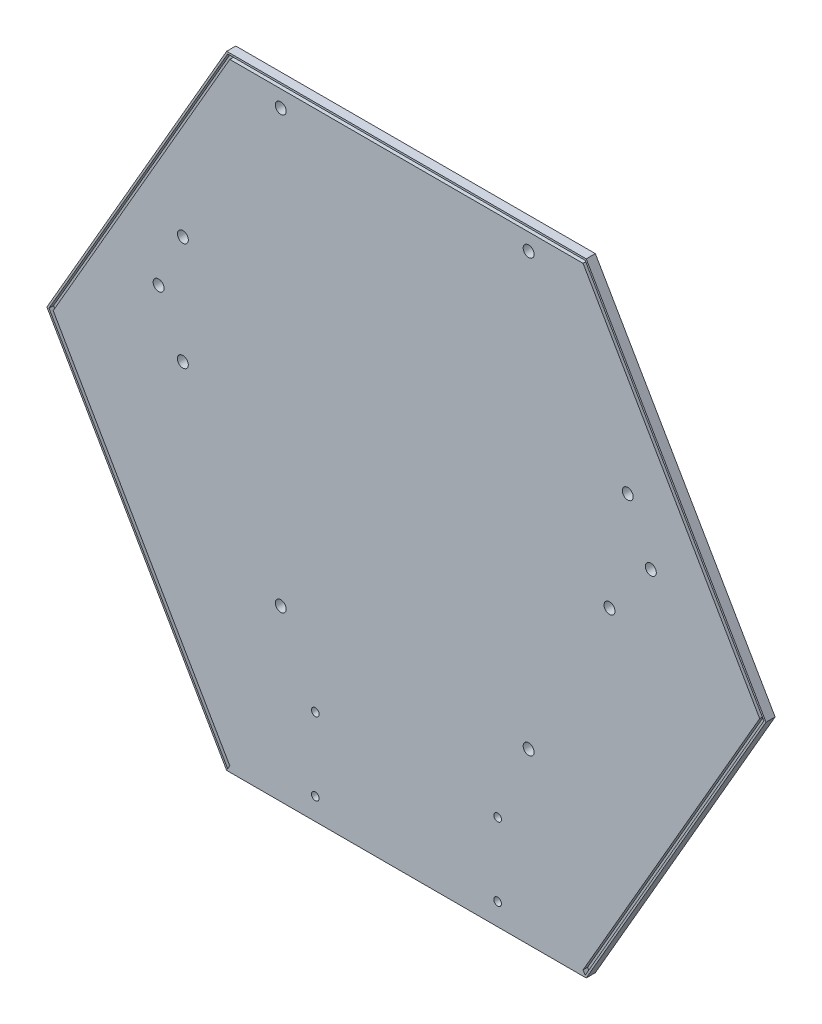
SolidWorks part; units mm, degrees
ref_plane "前视基准面" through (0, 0, 0) normal (0, 0, 1) x (1, 0, 0)
ref_plane "上视基准面" through (0, 0, 0) normal (0, 1, 0) x (1, 0, 0)
ref_plane "右视基准面" through (0, 0, 0) normal (1, 0, 0) x (0, 0, -1)
other "Configuration Table"
ref_plane "基准面1" through (0, 0, 20) normal (0, 0, 1) x (1, 0, 0)
sketch "草图51" plane through (0, 0, 20) normal (0, 0, 1) x (1, 0, 0)
  line L1 (198.1766, -40.9837) -> (99.5655, 129.8157)
  line L2 (99.5655, 129.8157) -> (-97.6567, 129.8157)
  line L3 (-97.6567, 129.8157) -> (-196.2678, -40.9837)
  line L4 (-196.2678, -40.9837) -> (-97.6567, -211.7832)
  line L5 (-97.6567, -211.7832) -> (99.5655, -211.7832)
  line L6 (99.5655, -211.7832) -> (198.1766, -40.9837)
  circle A0 centre (0.9544, -40.9837) radius 170.7994 construction
extrude "凸台-拉伸9" add sketch "草图51" along normal blind 5 separate body contours L4 L5 L6 L1 L2 L3
sketch "草图52" plane through (0, 0, 25) normal (0, 0, 1) x (1, 0, 0)
  line L0 (-195.1131, -40.9837) -> (-97.0793, 128.8157)
  line L1 (-97.0793, 128.8157) -> (98.9881, 128.8157)
  line L2 (98.9881, 128.8157) -> (197.0219, -40.9837)
  line L3 (197.0219, -40.9837) -> (98.9881, -210.7832)
  line L4 (98.9881, -210.7832) -> (97.8334, -208.7832)
  line L5 (97.8334, -208.7832) -> (194.7125, -40.9837)
  line L6 (194.7125, -40.9837) -> (97.8334, 126.8157)
  line L7 (97.8334, 126.8157) -> (-95.9246, 126.8157)
  line L8 (-95.9246, 126.8157) -> (-192.8037, -40.9837)
  line L9 (-192.8037, -40.9837) -> (-95.9246, -208.7832)
  line L10 (-95.9246, -208.7832) -> (-97.0793, -210.7832)
  line L11 (-97.0793, -210.7832) -> (-195.1131, -40.9837)
  line L12 (-196.2678, -40.9837) -> (-97.6567, -211.7832) construction
  line L13 (-97.6567, 129.8157) -> (-196.2678, -40.9837) construction
  line L14 (99.5655, 129.8157) -> (-97.6567, 129.8157) construction
  line L15 (198.1766, -40.9837) -> (99.5655, 129.8157) construction
  line L16 (99.5655, -211.7832) -> (198.1766, -40.9837) construction
  line L17 (-97.0793, -210.7832) -> (98.9881, -210.7832) construction
  line L18 (-196.2678, -40.9837) -> (-195.1131, -40.9837) construction
  line L19 (-97.6567, -211.7832) -> (99.5655, -211.7832) construction
  line L20 (-195.1131, -40.9837) -> (-192.8037, -40.9837) construction
  line L21 (-97.6567, 129.8157) -> (-97.0793, 128.8157) construction
  line L22 (-95.9246, 126.8157) -> (-97.0793, 128.8157) construction
  dimension "D1" = 1
  dimension "D2" = 1
  dimension "D3" = 2
  dimension "D4" = 2
  dimension "D5" = 2
  dimension "D6" = 1
  dimension "D7" = 1
  dimension "D8" = 2
  dimension "D9" = 1
  dimension "D10" = 2
  dimension "D11" = 1
  dimension "D12" = 60
  dimension "D13" = 60
extrude "切除-拉伸7" cut sketch "草图52" against normal blind 2.5 contours L11 L0 L1 L2 L3 L4 L5 L6 L7 L8 L9 L10
sketch "草图53" plane through (0, 0, 20) normal (0, 0, -1) x (-1, 0, 0)
  circle A0 centre (-67.98, -118.86) radius 3
  circle A1 centre (-67.98, -118.86) radius 3
  circle A2 centre (-67.98, 117.66) radius 3
  circle A3 centre (67.98, 117.66) radius 3
  circle A4 centre (-112.33, -29.68) radius 3
  circle A5 centre (121.69, -29.68) radius 3
  circle A6 centre (-135, 0) radius 3
  circle A7 centre (135, 0) radius 3
  circle A8 centre (-122.33, 29.64) radius 3
  circle A9 centre (121.69, 29.64) radius 3
  circle A10 centre (67.98, -118.86) radius 3
extrude "切除-拉伸12" cut sketch "草图53" against normal blind 5 contours A2 | A8 | A6 | A4 | A0 | A10 | A5 | A7 | A9 | A3
sketch "草图54" plane through (0, 0, 20) normal (0, 0, 1) x (1, 0, 0)
  line L0 (0.9544, 126.8157) -> (0.9544, -211.7832) construction
  line L1 (97.8334, 126.8157) -> (-95.9246, 126.8157) construction
  line L2 (-97.6567, -211.7832) -> (99.5655, -211.7832) construction
  circle A0 centre (-49.0456, -199.7832) radius 2.1
  circle A1 centre (50.9544, -199.7832) radius 2.1
  circle A2 centre (-49.0456, -159.7832) radius 2.1
  circle A3 centre (50.9544, -159.7832) radius 2.1
  dimension "D3" = 50
  dimension "D1" = 12
  dimension "D2" = 50
  dimension "D4" = 40
extrude "切除-拉伸14" cut sketch "草图54" along normal through all
